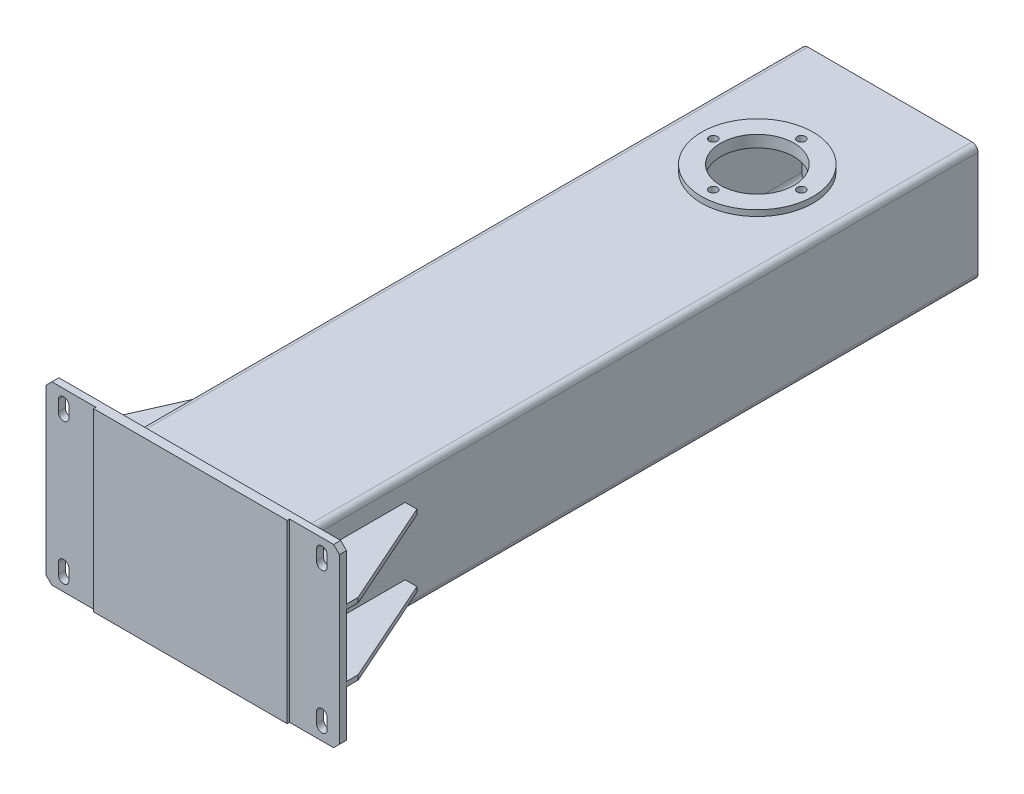
SolidWorks part; units mm, degrees
material "Q235"
ref_plane "前视基准面" through (0, 0, 0) normal (0, 0, 1) x (1, 0, 0)
ref_plane "上视基准面" through (0, 0, 0) normal (0, 1, 0) x (1, 0, 0)
ref_plane "右视基准面" through (0, 0, 0) normal (1, 0, 0) x (0, 0, -1)
sketch "草图1" plane through (0, 0, 0) normal (0, 0, 1) x (1, 0, 0)
  line L0 (-130, 90) -> (130, 90)
  line L1 (-140, 100) -> (140, 100)
  line L2 (-150, 90) -> (-150, -90)
  line L3 (-140, -100) -> (140, -100)
  line L4 (150, 90) -> (150, -90)
  line L5 (-150, 100) -> (150, -100) construction
  line L6 (-150, -100) -> (150, 100) construction
  line L7 (140, 80) -> (140, -80)
  line L8 (-130, -90) -> (130, -90)
  line L9 (-140, 80) -> (-140, -80)
  line L10 (-150, 100) -> (150, 100) construction
  line L11 (150, 100) -> (150, -100) construction
  line L12 (-140, 90) -> (140, 90) construction
  line L13 (140, 90) -> (140, -90) construction
  line L14 (-150, -100) -> (150, -100) construction
  line L15 (-140, -90) -> (140, -90) construction
  line L16 (-150, 100) -> (-150, -100) construction
  line L17 (-140, 90) -> (-140, -90) construction
  arc A0 (140, 100) -> (150, 90) centre (140, 90) cw
  arc A1 (130, 90) -> (140, 80) centre (130, 80) cw
  arc A2 (140, -100) -> (150, -90) centre (140, -90) ccw
  arc A3 (140, -80) -> (130, -90) centre (130, -80) cw
  arc A4 (-150, -90) -> (-140, -100) centre (-140, -90) ccw
  arc A5 (-130, -90) -> (-140, -80) centre (-130, -80) cw
  arc A6 (-140, 100) -> (-150, 90) centre (-140, 90) ccw
  arc A7 (-130, 90) -> (-140, 80) centre (-130, 80) ccw
  point P0 (0, 0)
  dimension "D3" = 10
  dimension "D1" = 300
  dimension "D2" = 200
  dimension "D4" = 10
extrude "凸台-拉伸1" add sketch "草图1" along normal blind 1176
sketch "草图2" plane through (0, 0, 1176) normal (0, 0, 1) x (1, 0, 0)
  line L1 (250, -150) -> (-250, -150)
  line L2 (250, -150) -> (250, 150)
  line L3 (250, 150) -> (-250, 150)
  line L4 (-250, -150) -> (-250, 150)
  line L5 (250, -150) -> (-250, 150) construction
  line L6 (250, 150) -> (-250, -150) construction
  point P0 (0, 0)
  dimension "D1" = 500
  dimension "D2" = 300
extrude "凸台-拉伸2" add sketch "草图2" along normal blind 16 separate body
sketch "草图4" plane through (0, -100, 0) normal (0, -1, 0) x (1, 0, 0)
  line L0 (0, -165) -> (0, 165) construction
  line L1 (-250, 1192) -> (250, 1192) construction
  circle A0 centre (0, 226) radius 95
  dimension "D1" = 966
  dimension "D2" = 190
extrude "切除-拉伸2" cut sketch "草图4" against normal through all
sketch "草图5" plane through (0, -100, 0) normal (0, -1, 0) x (1, 0, 0)
  circle A0 centre (0, 226) radius 62.5
  circle A1 centre (0, 226) radius 95
  dimension "D1" = 190
  dimension "D2" = 125
extrude "凸台-拉伸3" add sketch "草图5" along normal blind 10 and the other way blind 10 separate body
sketch "草图6" plane through (0, 100, 0) normal (0, 1, 0) x (1, 0, 0)
  circle A0 centre (0, -226) radius 95
  circle A1 centre (0, -226) radius 62.5
  dimension "D1" = 125
  dimension "D2" = 190
extrude "凸台-拉伸4" add sketch "草图6" along normal blind 10 and the other way blind 10 separate body
hole_wizard "M16 螺纹孔1" positions "草图8" profile "草图7" tap size "M16" standard "GB" end condition through all
sketch "草图8" plane through (0, 110, 0) normal (0, 1, 0) x (-1, 0, 0)
  line L0 (0, 165) -> (0, -165) construction
  circle A0 centre (0, 226) radius 62.5 construction
  point P0 (0, 151)
  dimension "D1" = 75
  dimension "D2" = 0
cosmetic thread "孔螺蚊线1" parameters "D2"=16
sketch "草图7" plane through (0, 110, 151) normal (1, 0, 0) x (0, 0, 1)
  line L0 (0, 0) -> (0, 260)
  line L1 (0, 260) -> (7, 260)
  line L2 (7, 260) -> (7, 0)
  line L5 (7, 0) -> (0, 0)
  line L11 (0, -6.35) -> (0, 107.95) construction
  dimension "通孔螺纹孔钻头直径" = 14
  dimension "通孔螺纹孔钻头深度" = 260
pattern_circular "阵列(圆周)1" count 4 over 360 about axis through (0, 0, 226) along (0, 1, 0) of "M16 螺纹孔1"
hole_wizard "M16 螺纹孔2" positions "草图10" profile "草图9" tap size "M16" standard "GB"
sketch "草图10" plane through (0, -110, 0) normal (0, -1, 0) x (1, 0, 0)
  line L0 (0, -165) -> (0, 165) construction
  circle A0 centre (0, 226) radius 62.5 construction
  point P0 (0, 151)
  dimension "D1" = 75
  dimension "D2" = 0
sketch "草图9" plane through (0, -110, 151) normal (1, 0, 0) x (0, 0, -1)
  line L0 (0, 0) -> (0, 42.206)
  line L1 (0, 42.206) -> (7, 38)
  line L2 (7, 38) -> (7, 0)
  line L5 (7, 0) -> (0, 0)
  line L10 (0, 42.206) -> (-7, 38) construction
  line L11 (0, -6.35) -> (0, 107.95) construction
  dimension "螺纹孔钻头直径" = 14
  dimension "螺纹孔钻头深度" = 38
  dimension "导头角度" = 118
cosmetic thread "孔螺蚊线2" parameters "D1"=30, "D2"=16
pattern_circular "阵列(圆周)2" count 4 over 360 about axis through (0, 0, 226) along (0, 1, 0) of "M16 螺纹孔2"
chamfer "倒角1" distance 5 angle 45 1 edges at (95, -90, 226)
chamfer "倒角2" distance 5 angle 45 1 edges at (0, 90, 321)
sketch "草图11" plane through (0, 0, 1192) normal (0, 0, 1) x (1, 0, 0)
  line L0 (250, 150) -> (-250, 150) construction
  line L1 (165, -150) -> (-165, -150)
  line L2 (165, -150) -> (165, 150)
  line L3 (165, 150) -> (-165, 150)
  line L4 (-165, -150) -> (-165, 150)
  line L5 (165, -150) -> (-165, 150) construction
  line L6 (165, 150) -> (-165, -150) construction
  line L7 (-250, 150) -> (-250, -150) construction
  point P0 (0, 0)
  dimension "D1" = 85
extrude "切除-拉伸3" cut sketch "草图11" against normal blind 4 flip side to cut
chamfer "倒角3" distance 10 angle 45 4 edges at (250, 150, 1182) (250, -150, 1182) (-250, -150, 1182) (-250, 150, 1182)
sketch "草图12" plane through (0, 0, 1176) normal (0, 0, -1) x (-1, 0, 0)
  line L0 (-250, -140) -> (-250, 140) construction
  line L1 (-250, 61.1147) -> (-150, 61.1147)
  line L2 (-250, 61.1147) -> (-250, 53.1147)
  line L3 (-250, 53.1147) -> (-150, 53.1147)
  line L4 (-150, 61.1147) -> (-150, 53.1147)
  line L5 (-250, 61.1147) -> (-150, 53.1147) construction
  line L6 (-250, 53.1147) -> (-150, 61.1147) construction
  line L7 (-150, -90) -> (-150, 90) construction
  point P0 (-200, 57.1147)
  dimension "D1" = 8
extrude "凸台-拉伸5" add sketch "草图12" along normal blind 200 separate body
sketch "草图13" plane through (0, 53.1147, 0) normal (0, -1, 0) x (1, 0, 0)
  line L0 (150, 1176) -> (155, 1176)
  line L1 (250, 1176) -> (150, 1176) construction
  line L2 (155, 1176) -> (150, 1171)
  line L3 (150, 976) -> (150, 1176) construction
  line L4 (150, 1171) -> (150, 1176)
  line L5 (250, 1156) -> (250, 976)
  line L6 (250, 976) -> (250, 1176) construction
  line L7 (250, 976) -> (170, 976)
  line L8 (250, 976) -> (150, 976) construction
  line L9 (170, 976) -> (250, 1156)
  dimension "D1" = 5
  dimension "D2" = 5
  dimension "D3" = 20
  dimension "D4" = 20
extrude "切除-拉伸4" cut sketch "草图13" against normal through all
mirror "镜向1" about plane through (0, 0, 0) normal (0, 1, 0) of bodies 115
mirror "镜向2" about plane through (0, 0, 0) normal (1, 0, 0) of bodies 116 115
sketch "草图16" plane through (0, 0, 0) normal (0, 0, -1) x (-1, 0, 0)
  line L1 (130, -90) -> (-130, -90)
  line L2 (140, -80) -> (140, 80)
  line L3 (130, 90) -> (-130, 90)
  line L4 (-140, -80) -> (-140, 80)
  line L5 (140, -90) -> (-140, 90) construction
  line L6 (140, 90) -> (-140, -90) construction
  arc A0 (-130, -90) -> (-140, -80) centre (-130, -80) cw
  arc A1 (130, -90) -> (140, -80) centre (130, -80) ccw
  arc A2 (140, 80) -> (130, 90) centre (130, 80) ccw
  arc A3 (-130, 90) -> (-140, 80) centre (-130, 80) ccw
  point P0 (0, 0)
  dimension "D1" = 10
extrude "凸台-拉伸6" add sketch "草图16" against normal blind 10 separate body
hole_wizard "M16 螺纹孔3" positions "草图18" profile "草图17" tap size "M16" standard "GB"
sketch "草图18" plane through (0, 0, 0) normal (0, 0, -1) x (-1, 0, 0)
  line L0 (-140, 100) -> (140, 100) construction
  line L1 (-150, -90) -> (-150, 90) construction
  line L2 (150, 90) -> (150, -90) construction
  line L3 (140, -100) -> (-140, -100) construction
  point P0 (120, -70)
  point P1 (-120, 70)
  dimension "D1" = 30
  dimension "D2" = 30
  dimension "D3" = 30
  dimension "D4" = 30
sketch "草图17" plane through (-120, -70, 0) normal (1, 0, 0) x (0, 1, 0)
  line L0 (0, 0) -> (0, 42.206)
  line L1 (0, 42.206) -> (7, 38)
  line L2 (7, 38) -> (7, 0)
  line L5 (7, 0) -> (0, 0)
  line L10 (0, 42.206) -> (-7, 38) construction
  line L11 (0, -6.35) -> (0, 107.95) construction
  dimension "螺纹孔钻头直径" = 14
  dimension "螺纹孔钻头深度" = 38
  dimension "导头角度" = 118
cosmetic thread "孔螺蚊线3" parameters "D1"=10, "D2"=16
cosmetic thread "孔螺蚊线4" parameters "D1"=10, "D2"=16
sketch "草图19" plane through (0, 0, 0) normal (0, 0, -1) x (-1, 0, 0)
  line L1 (-75, 50) -> (75, 50)
  line L2 (-75, 50) -> (-75, -50)
  line L3 (-75, -50) -> (75, -50)
  line L4 (75, 50) -> (75, -50)
  line L5 (-75, 50) -> (75, -50) construction
  line L6 (-75, -50) -> (75, 50) construction
  point P0 (0, 0)
  dimension "D1" = 150
  dimension "D2" = 100
extrude "切除-拉伸5" cut sketch "草图19" against normal blind 20
sketch "草图20" plane through (150, 0, 0) normal (1, 0, 0) x (0, 0, -1)
  line L0 (-1176, -90) -> (-1176, 90) construction
  circle A0 centre (-1076, 0) radius 25
  dimension "D1" = 50
  dimension "D2" = 100
extrude "切除-拉伸6" cut sketch "草图20" against normal blind 10
fillet "圆角1" radius 10 4 edges at (-75, 50, 5) (-75, -50, 5) (75, -50, 5) (75, 50, 5)
hole_wizard "M5 螺纹孔1" positions "草图22" profile "草图21" tap size "M5" standard "GB"
sketch "草图22" plane through (0, 0, 0) normal (0, 0, -1) x (-1, 0, 0)
  point P1 (80, 55)
  point P4 (80, -55)
  point P8 (-80, -55)
  point P12 (-80, 55)
sketch "草图21" plane through (-80, 55, 0) normal (1, 0, 0) x (0, 1, 0)
  line L0 (0, 0) -> (0, 15.2618)
  line L1 (0, 15.2618) -> (2.1, 14)
  line L2 (2.1, 14) -> (2.1, 0)
  line L5 (2.1, 0) -> (0, 0)
  line L10 (0, 15.2618) -> (-2.1, 14) construction
  line L11 (0, -6.35) -> (0, 107.95) construction
  dimension "螺纹孔钻头直径" = 4.2
  dimension "螺纹孔钻头深度" = 14
  dimension "导头角度" = 118
cosmetic thread "孔螺蚊线5" parameters "D1"=10, "D2"=5
cosmetic thread "孔螺蚊线6" parameters "D1"=10, "D2"=5
cosmetic thread "孔螺蚊线7" parameters "D1"=10, "D2"=5
cosmetic thread "孔螺蚊线8" parameters "D1"=10, "D2"=5
sketch "草图23" plane through (0, 0, 1176) normal (0, 0, -1) x (-1, 0, 0)
  line L0 (-240, 150) -> (240, 150) construction
  line L1 (-250, -140) -> (-250, 140) construction
  line L2 (240, -150) -> (-240, -150) construction
  line L3 (250, 140) -> (250, -140) construction
  circle A0 centre (-220, 120) radius 9
  circle A1 centre (-220, -120) radius 9
  circle A2 centre (220, -120) radius 9
  circle A3 centre (220, 120) radius 9
  dimension "D1" = 18
  dimension "D2" = 30
  dimension "D3" = 30
  dimension "D4" = 30
  dimension "D5" = 30
  dimension "D6" = 30
  dimension "D7" = 30
  dimension "D8" = 30
  dimension "D9" = 30
extrude "切除-拉伸7" cut sketch "草图23" against normal through all
sketch "草图24" plane through (0, 0, 1176) normal (0, 0, -1) x (-1, 0, 0)
  line L0 (-220, 129) -> (-220, 111) construction
  line L1 (-211, 129) -> (-211, 111)
  line L2 (-229, 129) -> (-229, 111)
  line L3 (-220, -111) -> (-220, -129) construction
  line L4 (-211, -111) -> (-211, -129)
  line L5 (-229, -111) -> (-229, -129)
  line L6 (0, 150) -> (0, -150) construction
  line L7 (-240, 150) -> (240, 150) construction
  line L8 (240, -150) -> (-240, -150) construction
  line L9 (220, 129) -> (220, 111) construction
  line L10 (211, 129) -> (211, 111)
  line L11 (229, 129) -> (229, 111)
  line L12 (220, -111) -> (220, -129) construction
  line L13 (211, -111) -> (211, -129)
  line L14 (229, -111) -> (229, -129)
  circle A0 centre (-220, 120) radius 9 construction
  arc A1 (-211, 129) -> (-229, 129) centre (-220, 129) ccw
  arc A2 (-229, 111) -> (-211, 111) centre (-220, 111) ccw
  circle A3 centre (-220, -120) radius 9 construction
  arc A4 (-211, -111) -> (-229, -111) centre (-220, -111) ccw
  arc A5 (-229, -129) -> (-211, -129) centre (-220, -129) ccw
  arc A6 (211, 129) -> (229, 129) centre (220, 129) cw
  arc A7 (229, 111) -> (211, 111) centre (220, 111) cw
  arc A8 (211, -111) -> (229, -111) centre (220, -111) cw
  arc A9 (229, -129) -> (211, -129) centre (220, -129) cw
  point P5 (-220, 120)
  point P15 (-220, -120)
  point P28 (220, 120)
  point P35 (220, -120)
extrude "切除-拉伸8" cut sketch "草图24" against normal through all
